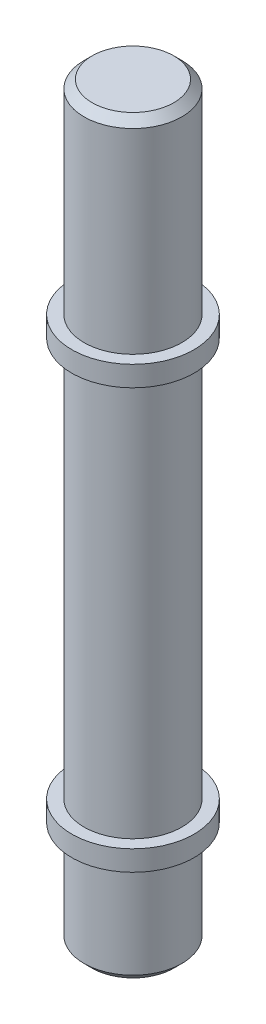
SolidWorks part; units mm, degrees
ref_plane "Front Plane" through (0, 0, 0) normal (0, 0, 1) x (1, 0, 0)
ref_plane "Top Plane" through (0, 0, 0) normal (0, 1, 0) x (1, 0, 0)
ref_plane "Right Plane" through (0, 0, 0) normal (1, 0, 0) x (0, 0, -1)
sketch "Sketch1" plane through (0, 0, 0) normal (0, 0, 1) x (1, 0, 0)
  line L0 (0, 95.6995) -> (0, -88.3005) construction
  line L1 (0, -88.3005) -> (12, -88.3005)
  line L2 (12, -88.3005) -> (12, -62.3005)
  line L3 (12, -62.3005) -> (15, -62.3005)
  line L4 (15, -62.3005) -> (15, -57.3005)
  line L5 (15, -57.3005) -> (12, -57.3005)
  line L6 (12, -57.3005) -> (12, 40.6995)
  line L7 (12, 40.6995) -> (15, 40.6995)
  line L8 (15, 40.6995) -> (15, 45.6995)
  line L9 (15, 45.6995) -> (12, 45.6995)
  line L10 (12, 45.6995) -> (12, 95.6995)
  line L11 (12, 95.6995) -> (0, 95.6995)
  line L12 (0, 95.6995) -> (0, -88.3005)
  dimension "D1" = 184
  dimension "D2" = 5
  dimension "D3" = 5
  dimension "D4" = 26
  dimension "D5" = 98
  dimension "D6" = 50
  dimension "D7" = 30
  dimension "D8" = 24
  dimension "D9" = 24
  dimension "D10" = 30
  dimension "D11" = 24
revolve "Revolve1" add sketch "Sketch1" angle 360 about L0
chamfer "Chamfer1" distance 2 angle 45 2 edges at (-12, -88.3005, 0) (-12, 95.6995, 0)
cosmetic thread "Cosmetic Thread1"
cosmetic thread "Cosmetic Thread2"
